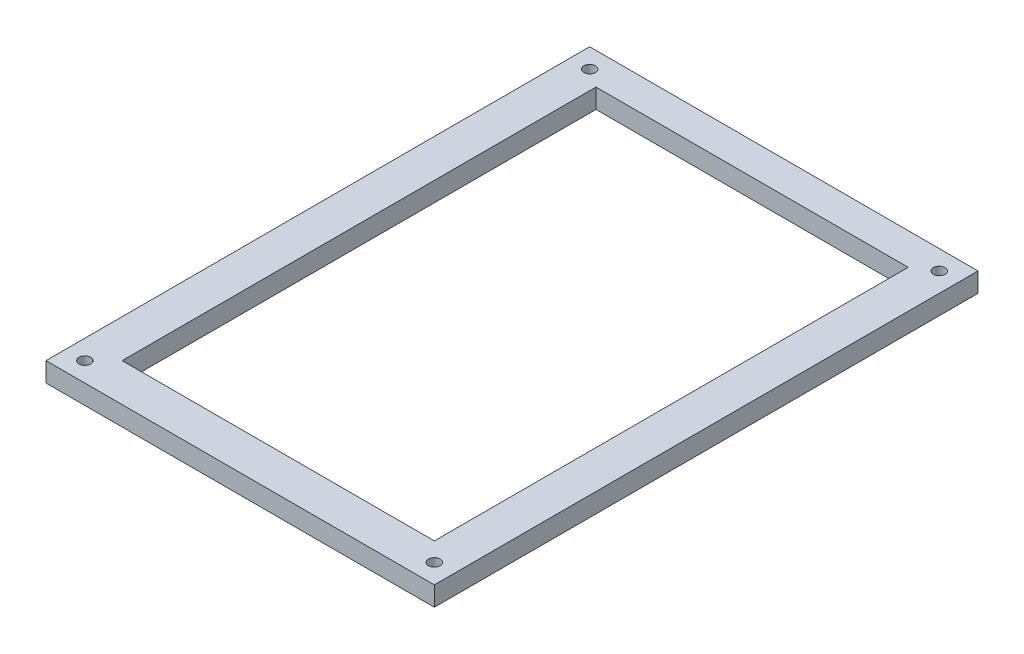
SolidWorks part; units mm, degrees
ref_plane "Front" through (0, 0, 0) normal (0, 0, 1) x (1, 0, 0)
ref_plane "Top" through (0, 0, 0) normal (0, 1, 0) x (1, 0, 0)
ref_plane "Right" through (0, 0, 0) normal (1, 0, 0) x (0, 0, -1)
sketch "Sketch1" plane through (0, 0, 0) normal (0, 1, 0) x (1, 0, 0)
  line L1 (0, 0) -> (127, 0)
  line L2 (0, 0) -> (0, 177.8)
  line L3 (0, 177.8) -> (127, 177.8)
  line L4 (127, 0) -> (127, 177.8)
  dimension "D1" = 127
  dimension "D2" = 177.8
extrude "Boss-Extrude1" add sketch "Sketch1" along normal blind 6.35
sketch "Sketch2" plane through (0, 6.35, 0) normal (0, 1, 0) x (1, 0, 0)
  line L0 (0, 0) -> (127, 0) construction
  line L1 (12.446, 167.4117) -> (114.554, 167.4117)
  line L2 (12.446, 167.4117) -> (12.446, 12.446)
  line L3 (12.446, 12.446) -> (114.554, 12.446)
  line L4 (114.554, 167.4117) -> (114.554, 12.446)
  line L5 (0, 177.8) -> (0, 0) construction
  dimension "D1" = 102.108
  dimension "D2" = 154.9657
  dimension "D3" = 12.446
  dimension "D4" = 12.446
extrude "Cut-Extrude1" cut sketch "Sketch2" against normal through all
sketch "Sketch3" plane through (0, 6.35, 0) normal (0, 1, 0) x (1, 0, 0)
  line L0 (127, 177.8) -> (0, 177.8) construction
  line L1 (0, 177.8) -> (0, 0) construction
  line L2 (63.5, 177.8) -> (63.5, 0) construction
  line L3 (0, 0) -> (127, 0) construction
  line L4 (0, 88.9) -> (127, 88.9) construction
  line L5 (127, 0) -> (127, 177.8) construction
  circle A0 centre (6.35, 171.45) radius 1.905
  circle A1 centre (6.35, 6.35) radius 1.905
  circle A2 centre (120.65, 6.35) radius 1.905
  circle A3 centre (120.65, 171.45) radius 1.905
  dimension "D1" = 3.81
  dimension "D2" = 6.35
  dimension "D3" = 6.35
extrude "Cut-Extrude2" cut sketch "Sketch3" against normal through all
